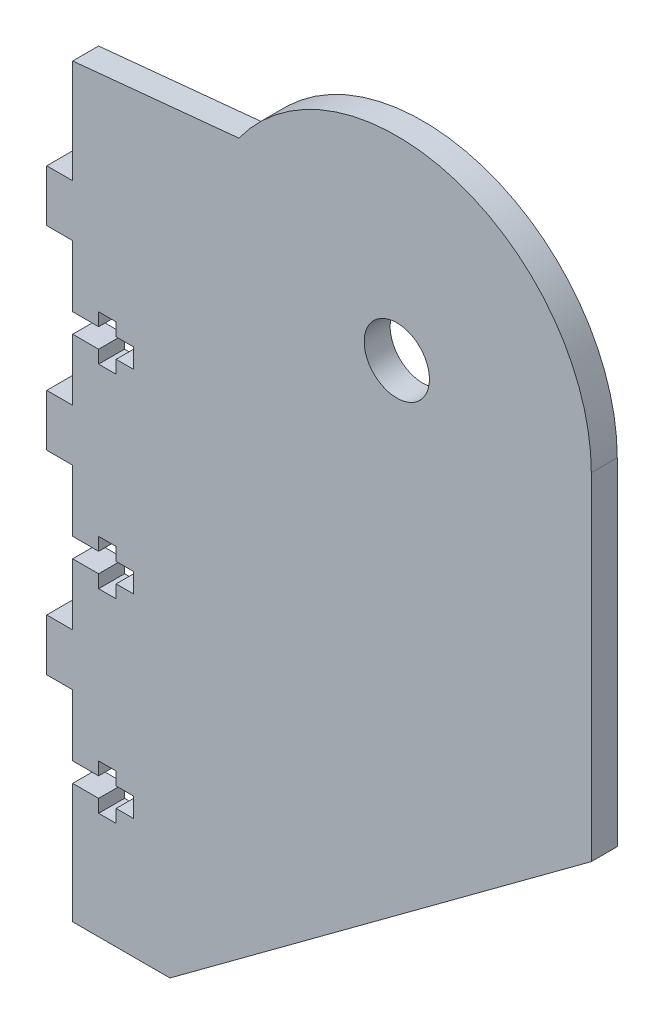
SolidWorks part; units mm, degrees
ref_plane "前视基准面" through (0, 0, 0) normal (0, 0, 1) x (1, 0, 0)
ref_plane "上视基准面" through (0, 0, 0) normal (0, 1, 0) x (1, 0, 0)
ref_plane "右视基准面" through (0, 0, 0) normal (1, 0, 0) x (0, 0, -1)
sketch "草图1" plane through (0, 0, 0) normal (0, 0, 1) x (1, 0, 0)
  line L1 (298.5429, -0.1457) -> (298.5429, -100.1457) construction
  line L4 (348.5429, -0.1457) -> (428.5429, -0.1457) construction
  line L11 (348.5429, -0.1457) -> (298.5429, -0.1457) construction
  line L15 (298.5429, -51.6457) -> (302.5429, -51.6457)
  line L16 (302.5429, -51.6457) -> (302.5429, -53.6442)
  line L17 (302.5429, -53.6442) -> (305.2429, -53.6442)
  line L18 (305.2429, -53.6442) -> (305.2429, -51.6457)
  line L19 (305.2429, -51.6457) -> (307.9429, -51.6457)
  line L20 (307.9429, -51.6457) -> (307.9429, -48.6457)
  line L21 (307.9429, -48.6457) -> (305.2429, -48.6457)
  line L22 (305.2429, -48.6457) -> (305.2429, -46.6473)
  line L23 (305.2429, -46.6473) -> (302.5429, -46.6473)
  line L24 (302.5429, -46.6473) -> (302.5429, -48.6457)
  line L25 (302.5429, -48.6457) -> (298.5429, -48.6457)
  line L27 (298.5429, -50.1457) -> (302.5429, -50.1457) construction
  line L28 (298.5429, -65.1457) -> (302.5429, -65.1457) construction
  line L29 (302.5429, -69.1457) -> (294.5429, -69.1457) construction
  line L30 (302.5429, -69.1457) -> (302.5429, -61.1457) construction
  line L31 (302.5429, -61.1457) -> (294.5429, -61.1457) construction
  line L32 (294.5429, -69.1457) -> (294.5429, -61.1457)
  line L33 (302.5429, -69.1457) -> (294.5429, -61.1457) construction
  line L34 (302.5429, -61.1457) -> (294.5429, -69.1457) construction
  line L35 (302.5429, -81.6457) -> (298.5429, -81.6457)
  line L36 (298.5429, -78.6457) -> (302.5429, -78.6457)
  line L37 (302.5429, -83.6442) -> (302.5429, -81.6457)
  line L38 (305.2429, -83.6442) -> (302.5429, -83.6442)
  line L39 (305.2429, -81.6457) -> (305.2429, -83.6442)
  line L40 (307.9429, -81.6457) -> (305.2429, -81.6457)
  line L41 (307.9429, -78.6457) -> (307.9429, -81.6457)
  line L42 (305.2429, -78.6457) -> (307.9429, -78.6457)
  line L43 (305.2429, -76.6473) -> (305.2429, -78.6457)
  line L44 (302.5429, -76.6473) -> (305.2429, -76.6473)
  line L45 (302.5429, -78.6457) -> (302.5429, -76.6473)
  line L46 (294.5429, -31.1457) -> (294.5429, -39.1457)
  line L47 (302.5429, -18.6457) -> (298.5429, -18.6457)
  line L48 (298.5429, -21.6457) -> (302.5429, -21.6457)
  line L49 (302.5429, -21.6457) -> (302.5429, -23.6442)
  line L50 (302.5429, -23.6442) -> (305.2429, -23.6442)
  line L51 (305.2429, -23.6442) -> (305.2429, -21.6457)
  line L52 (305.2429, -21.6457) -> (307.9429, -21.6457)
  line L53 (307.9429, -21.6457) -> (307.9429, -18.6457)
  line L54 (307.9429, -18.6457) -> (305.2429, -18.6457)
  line L55 (305.2429, -18.6457) -> (305.2429, -16.6473)
  line L56 (305.2429, -16.6473) -> (302.5429, -16.6473)
  line L57 (302.5429, -16.6473) -> (302.5429, -18.6457)
  line L58 (294.5429, -39.1457) -> (298.5429, -39.1457)
  line L59 (294.5429, -31.1457) -> (298.5429, -31.1457)
  line L60 (298.5429, -31.1457) -> (298.5429, -21.6457)
  line L61 (298.5429, -39.1457) -> (298.5429, -48.6457)
  line L62 (298.5429, -51.6457) -> (298.5429, -61.1457)
  line L63 (298.5429, -61.1457) -> (294.5429, -61.1457)
  line L64 (294.5429, -69.1457) -> (298.5429, -69.1457)
  line L65 (298.5429, -69.1457) -> (298.5429, -78.6457)
  line L66 (307.9429, -20.1457) -> (305.2429, -20.1457) construction
  line L67 (294.5429, -1.1457) -> (298.5429, -1.1457)
  line L68 (294.5429, -9.1457) -> (294.5429, -1.1457)
  line L69 (294.5429, -9.1457) -> (298.5429, -9.1457)
  line L70 (298.5429, -9.1457) -> (298.5429, -18.6457)
  line L71 (298.5429, -0.1457) -> (298.5429, 14.8543)
  line L72 (298.5429, 14.8543) -> (324.1861, 17.3685)
  line L73 (298.5429, -81.6457) -> (298.5429, -100.1457)
  line L74 (298.5429, -0.1457) -> (298.5429, -1.1457)
  line L75 (298.5429, -100.1457) -> (313.5429, -100.1457)
  line L77 (378.5429, -0.1457) -> (378.5429, -52.1022)
  line L78 (378.5429, -52.1022) -> (313.5429, -100.1457)
  circle A11 centre (348.5429, -0.1457) radius 5.03
  circle A14 centre (348.5429, -0.1457) radius 30 construction
  arc A19 (378.5429, -0.1457) -> (324.1861, 17.3685) centre (348.5429, -0.1457) ccw
  point P30 (298.5429, -65.1457)
  dimension "D1" = 100
  dimension "D3" = 3
  dimension "D4" = 10.06
  dimension "D5" = 2.7
  dimension "D6" = 50
  dimension "D7" = 80
  dimension "D8" = 4
  dimension "D9" = 1.5
  dimension "D10" = 15
  dimension "D11" = 8
  dimension "D12" = 8
extrude "凸台-拉伸1" add sketch "草图1" along normal blind 4
sketch "草图2" plane through (298.5429, 0, 0) normal (-1, 0, 0) x (0, 0, 1)
  line L0 (2, -21.6457) -> (2, -18.6457) construction
  line L1 (4, -21.6457) -> (0, -21.6457) construction
  line L2 (4, -18.6457) -> (0, -18.6457) construction
  circle A0 centre (2, -20.1457) radius 1.5
